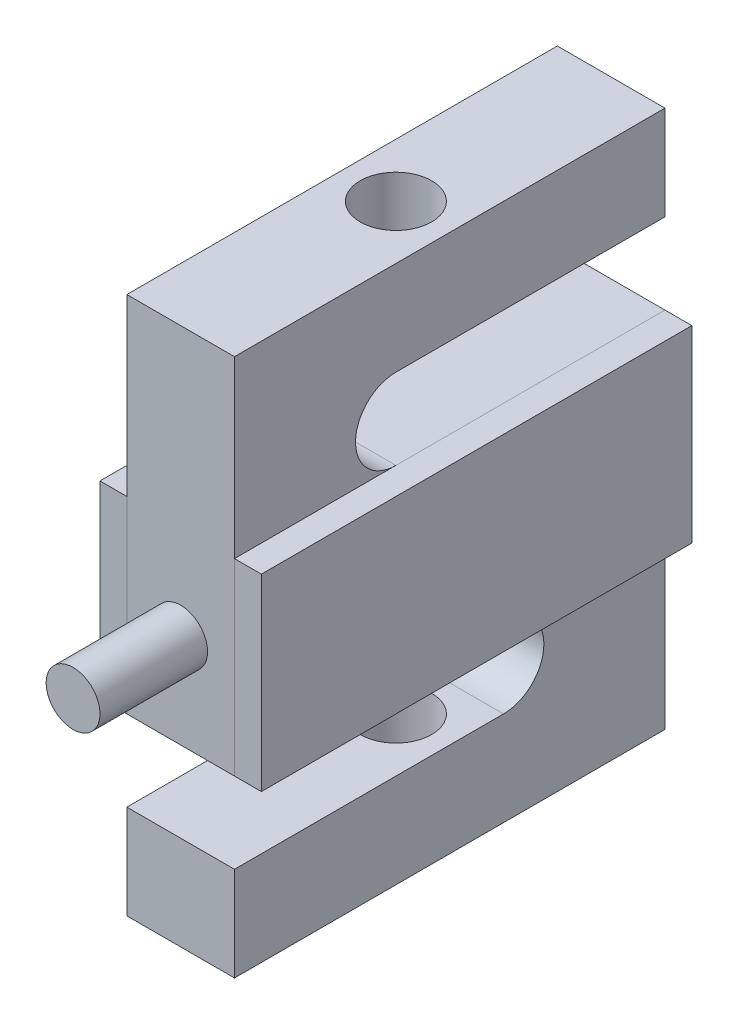
SolidWorks part; units mm, degrees
ref_plane "Front" through (0, 0, 0) normal (0, 0, 1) x (1, 0, 0)
ref_plane "Top" through (0, 0, 0) normal (0, 1, 0) x (1, 0, 0)
ref_plane "Right" through (0, 0, 0) normal (1, 0, 0) x (0, 0, -1)
sketch "Sketch1" plane through (0, 0, 0) normal (1, 0, 0) x (0, 0, -1)
  line L0 (50.8, 52.3875) -> (19.05, 52.3875)
  line L1 (0, 0) -> (50.8, 0)
  line L2 (0, 0) -> (0, 11.1125)
  line L3 (0, 63.5) -> (50.8, 63.5)
  line L4 (50.8, 0) -> (50.8, 42.8625)
  line L5 (19.05, 42.8625) -> (50.8, 42.8625)
  line L6 (0, 20.6375) -> (31.75, 20.6375)
  line L7 (31.75, 11.1125) -> (0, 11.1125)
  line L8 (50.8, 52.3875) -> (50.8, 63.5)
  line L9 (0, 20.6375) -> (0, 63.5)
  arc A0 (19.05, 52.3875) -> (19.05, 42.8625) centre (19.05, 47.625) ccw
  arc A1 (31.75, 20.6375) -> (31.75, 11.1125) centre (31.75, 15.875) cw
  dimension "D3" = 31.75
  dimension "D4" = 31.75
  dimension "D1" = 50.8
  dimension "D2" = 63.5
  dimension "D5" = 9.525
extrude "Extrude1" add sketch "Sketch1" along normal mid plane 12.7
sketch "Sketch2" plane through (6.35, 0, 0) normal (1, 0, 0) x (0, 0, -1)
  line L1 (50.8, 42.8625) -> (0, 42.8625)
  line L2 (50.8, 42.8625) -> (50.8, 20.6375)
  line L3 (50.8, 20.6375) -> (0, 20.6375)
  line L4 (0, 42.8625) -> (0, 20.6375)
extrude "Extrude2" add sketch "Sketch2" along normal blind 3.175 separate body
sketch "Sketch3" plane through (-6.35, 0, 0) normal (-1, 0, 0) x (0, 0, 1)
  line L4 (-50.8, 42.8625) -> (-50.8, 20.6375)
  line L5 (0, 42.8625) -> (-50.8, 42.8625)
  line L6 (0, 20.6375) -> (0, 42.8625)
  line L7 (-50.8, 20.6375) -> (0, 20.6375)
  line L8 (-50.8, 42.8625) -> (-50.8, 20.6375)
  line L9 (0, 42.8625) -> (-50.8, 42.8625)
  line L10 (0, 20.6375) -> (0, 42.8625)
  line L11 (-50.8, 20.6375) -> (0, 20.6375)
  dimension "D1" = 0
extrude "Extrude3" add sketch "Sketch3" along normal blind 3.175 separate body
hole_wizard "3/8-24 Tapped Hole1" positions "Sketch5" profile "Sketch4" tap size "3/8-24" standard "Ansi Inch" end condition up to next
sketch "Sketch5" plane through (0, 63.5, 0) normal (0, 1, 0) x (-1, 0, 0)
  line L0 (-6.35, 0) -> (6.35, 0) construction
  point P0 (0, -25.4)
  dimension "D1" = 25.4
sketch "Sketch4" plane through (0, 63.5, -25.4) normal (1, 0, 0) x (0, 0, 1)
  line L0 (0, 0) -> (0, 11.1125)
  line L1 (0, 11.1125) -> (4.2164, 11.1125)
  line L2 (4.2164, 11.1125) -> (4.2164, 0)
  line L5 (4.2164, 0) -> (0, 0)
  line L11 (0, -6.35) -> (0, 107.95) construction
  dimension "Thru Tap Drill Dia." = 8.4328
  dimension "Thru Tap Drill Depth" = 11.1125
cosmetic thread "Hole Thread1"
hole_wizard "3/8-24 Tapped Hole2" positions "Sketch7" profile "Sketch8" tap size "3/8-24" standard "Ansi Inch" end condition up to next
sketch "Sketch7" plane through (0, 0, 0) normal (0, -1, 0) x (1, 0, 0)
  point P0 (0, -25.4)
sketch "Sketch8" plane through (0, 0, -25.4) normal (1, 0, 0) x (0, 0, -1)
  line L0 (0, 0) -> (0, 11.1125)
  line L1 (0, 11.1125) -> (4.2164, 11.1125)
  line L2 (4.2164, 11.1125) -> (4.2164, 0)
  line L5 (4.2164, 0) -> (0, 0)
  line L11 (0, -6.35) -> (0, 107.95) construction
  dimension "Thru Tap Drill Dia." = 8.4328
  dimension "Thru Tap Drill Depth" = 11.1125
cosmetic thread "Hole Thread2"
sketch "Sketch10" plane through (0, 0, 0) normal (0, 0, 1) x (1, 0, 0)
  line L0 (6.35, 0) -> (-6.35, 0) construction
  circle A0 centre (0, 31.75) radius 3.175
  dimension "D1" = 6.35
  dimension "D2" = 31.75
extrude "Extrude4" add sketch "Sketch10" along normal blind 12.7
